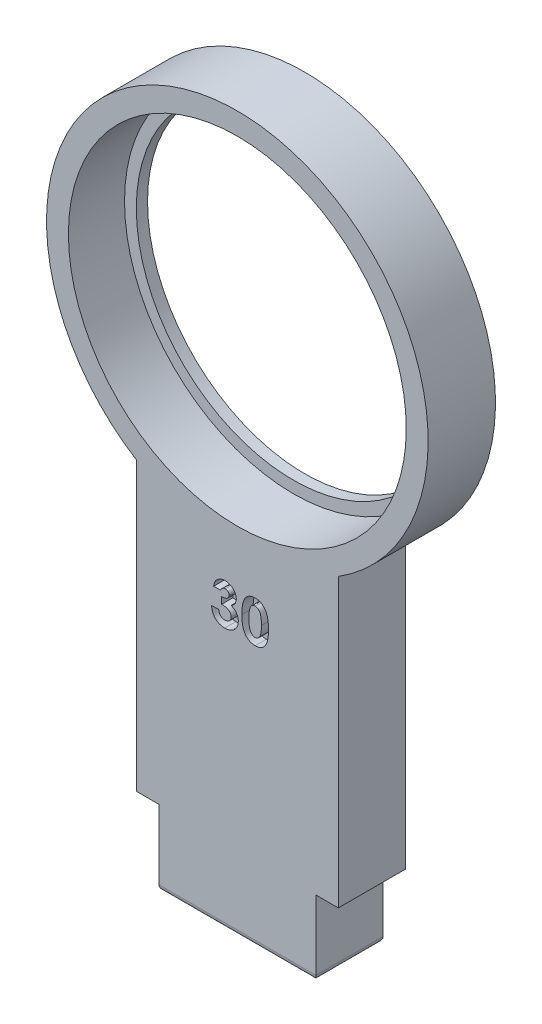
SolidWorks part; units mm, degrees
ref_plane "Front" through (0, 0, 0) normal (0, 0, 1) x (1, 0, 0)
ref_plane "Top" through (0, 0, 0) normal (0, 1, 0) x (1, 0, 0)
ref_plane "Right" through (0, 0, 0) normal (1, 0, 0) x (0, 0, -1)
sketch "Sketch1" plane through (0, 0, 0) normal (0, 0, 1) x (1, 0, 0)
  circle A0 centre (0, 0) radius 17
  dimension "D1" = 34
extrude "Boss-Extrude1" add sketch "Sketch1" along normal mid plane 6
sketch "Sketch2" plane through (0, 0, 3) normal (0, 0, 1) x (1, 0, 0)
  circle A0 centre (0, 0) radius 15.05
  dimension "D1" = 30.1
extrude "Cut-Extrude1" cut sketch "Sketch2" against normal blind 5
sketch "Sketch3" plane through (0, 0, -2) normal (0, 0, 1) x (1, 0, 0)
  circle A0 centre (0, 0) radius 14
  dimension "D1" = 28
extrude "Cut-Extrude2" cut sketch "Sketch3" against normal through all
sketch "Sketch4" plane through (0, 0, 0) normal (0, 0, 1) x (1, 0, 0)
  line L0 (-9, -14.4222) -> (-9, -40)
  line L1 (-9, -40) -> (9, -40)
  line L2 (9, -40) -> (9, -14.4222)
  circle A0 centre (0, 0) radius 17 construction
  arc A1 (-9, -14.4222) -> (9, -14.4222) centre (0, 0) ccw
  point P4 (0, -40)
  dimension "D1" = 18
  dimension "D2" = 40
extrude "Boss-Extrude2" add sketch "Sketch4" along normal mid plane 6
sketch "Sketch5" plane through (0, 0, 0) normal (0, 0, 1) x (1, 0, 0)
  line L1 (-9, -40) -> (9, -40) construction
  line L3 (7, -40) -> (-7, -40)
  line L4 (-7, -40) -> (-7, -46.7)
  line L5 (-7, -46.7) -> (7, -46.7)
  line L6 (7, -46.7) -> (7, -40)
  dimension "D1" = 14
  dimension "D2" = 6.7
  dimension "D3" = 7
extrude "Boss-Extrude3" add sketch "Sketch5" along normal mid plane 6
sketch "Sketch6" plane through (0, 0, 3) normal (0, 0, 1) x (1, 0, 0)
  text T0 "<b>30</b>"
extrude "Cut-Extrude3" cut sketch "Sketch6" against normal blind 1
fillet "Fillet1" radius 0.5 4 edges at (-7, -46.7, 0) (0, -46.7, -3) (0, -46.7, 3) (7, -46.7, 0)
